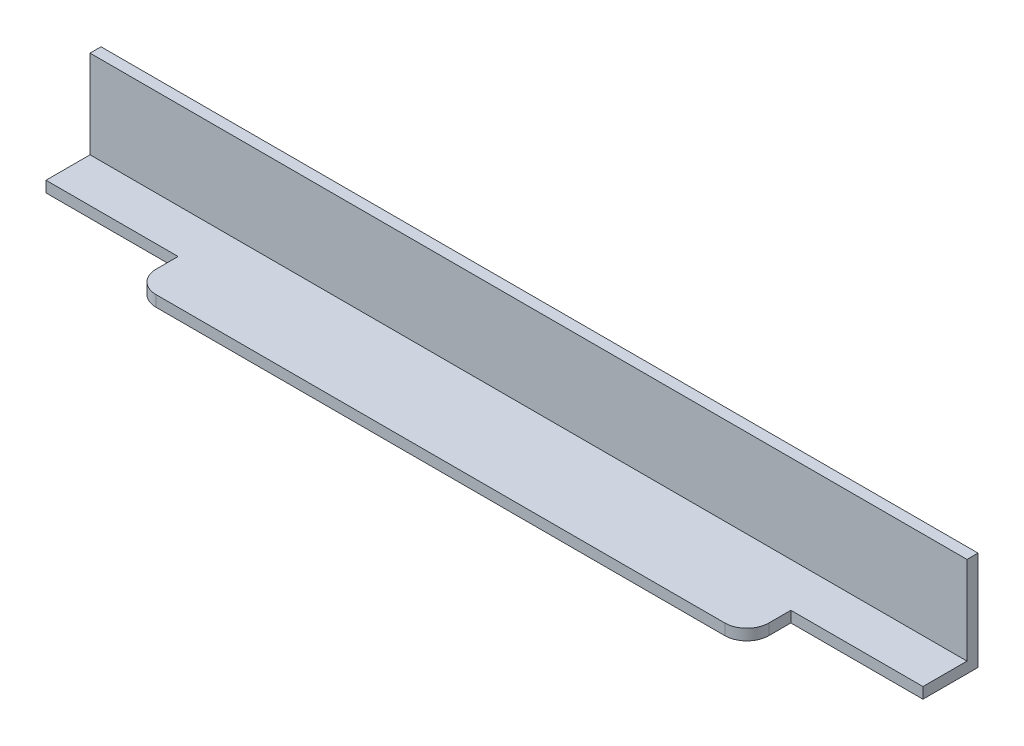
SolidWorks part; units mm, degrees
ref_plane "Front Plane" through (0, 0, 0) normal (0, 0, 1) x (1, 0, 0)
ref_plane "Top Plane" through (0, 0, 0) normal (0, 1, 0) x (1, 0, 0)
ref_plane "Right Plane" through (0, 0, 0) normal (1, 0, 0) x (0, 0, -1)
sketch "Sketch2" plane through (0, 0, 0) normal (0, 0, 1) x (1, 0, 0)
  line L1 (0, 0) -> (-239, 0)
  line L2 (0, 0) -> (0, -27)
  line L3 (0, -27) -> (-239, -27)
  line L4 (-239, 0) -> (-239, -27)
  dimension "D1" = 239
  dimension "D2" = 27
extrude "Boss-Extrude1" add sketch "Sketch2" along normal blind 3
sketch "Sketch3" plane through (0, 0, 3) normal (0, 0, 1) x (1, 0, 0)
  line L0 (0, -27) -> (0, 0) construction
  line L1 (-239, -27) -> (0, -27)
  line L2 (-239, -27) -> (-239, -24)
  line L3 (-239, -24) -> (0, -24)
  line L4 (0, -27) -> (0, -24)
  dimension "D1" = 3
extrude "Boss-Extrude2" add sketch "Sketch3" along normal blind 12
sketch "Sketch4" plane through (0, -24, 0) normal (0, 1, 0) x (1, 0, 0)
  line L0 (0, -15) -> (-239, -15) construction
  line L1 (-203, -15) -> (-36, -15)
  line L2 (-203, -15) -> (-203, -21)
  line L3 (-197, -27) -> (-42, -27)
  line L4 (-36, -15) -> (-36, -21)
  line L5 (-239, -15) -> (-239, -3) construction
  line L6 (0, -15) -> (0, -3) construction
  arc A0 (-42, -27) -> (-36, -21) centre (-42, -21) ccw
  arc A1 (-203, -21) -> (-197, -27) centre (-197, -21) ccw
  point P12 (-36, -27)
  dimension "D4" = 6
  dimension "D1" = 36
  dimension "D2" = 36
  dimension "D3" = 12
extrude "Boss-Extrude4" add sketch "Sketch4" against normal blind 3
